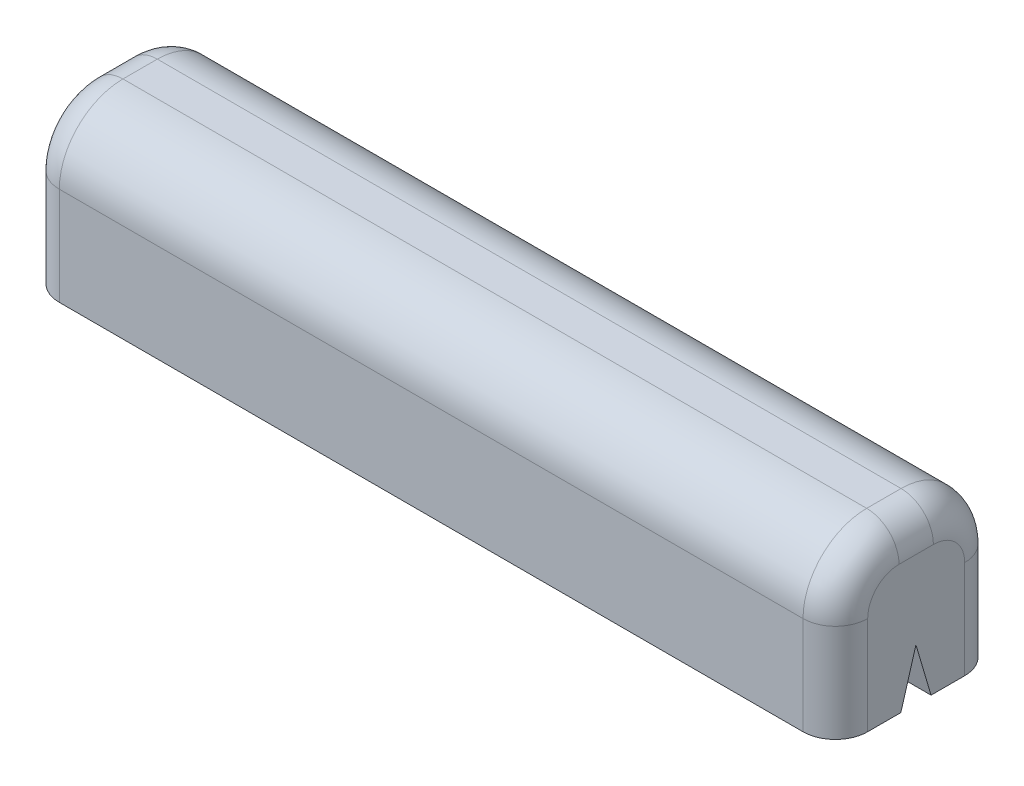
SolidWorks part; units mm, degrees
ref_plane "Front Plane" through (0, 0, 0) normal (0, 0, 1) x (1, 0, 0)
ref_plane "Top Plane" through (0, 0, 0) normal (0, 1, 0) x (1, 0, 0)
ref_plane "Right Plane" through (0, 0, 0) normal (1, 0, 0) x (0, 0, -1)
sketch "Sketch1" plane through (0, 0, 0) normal (1, 0, 0) x (0, 0, -1)
  line L1 (-4.75, 0) -> (-2.375, 8.0385)
  line L2 (-2.375, 8.0385) -> (0, 0)
  line L6 (-15.037, 0) -> (-15.037, 25.4)
  line L7 (-15.037, 25.4) -> (10.363, 25.4)
  line L15 (-4.75, 0) -> (-15.037, 0)
  line L16 (0, 0) -> (10.363, 0)
  line L17 (10.363, 25.4) -> (10.363, 0)
  dimension "D1" = 8.382
  dimension "D2" = 8.382
  dimension "D3" = 32.92
  dimension "D4" = 10.287
  dimension "D5" = 25.4
  dimension "D6" = 25.4
extrude "Boss-Extrude1" add sketch "Sketch1" along normal blind 127
fillet "Fillet1" radius 10 2 edges at (63.5, 25.4, 15.037) (63.5, 25.4, -10.363)
fillet "Fillet2" radius 5.08 10 edges at (0, 7.7, 15.037) (127, 7.7, 15.037) (0, 25.4, 2.337) (0, 22.4711, 12.1081) (127, 22.4711, 12.1081) (127, 25.4, 2.337) (0, 7.7, -10.363) (0, 22.4711, -7.4341) (127, 7.7, -10.363) (127, 22.4711, -7.4341)
